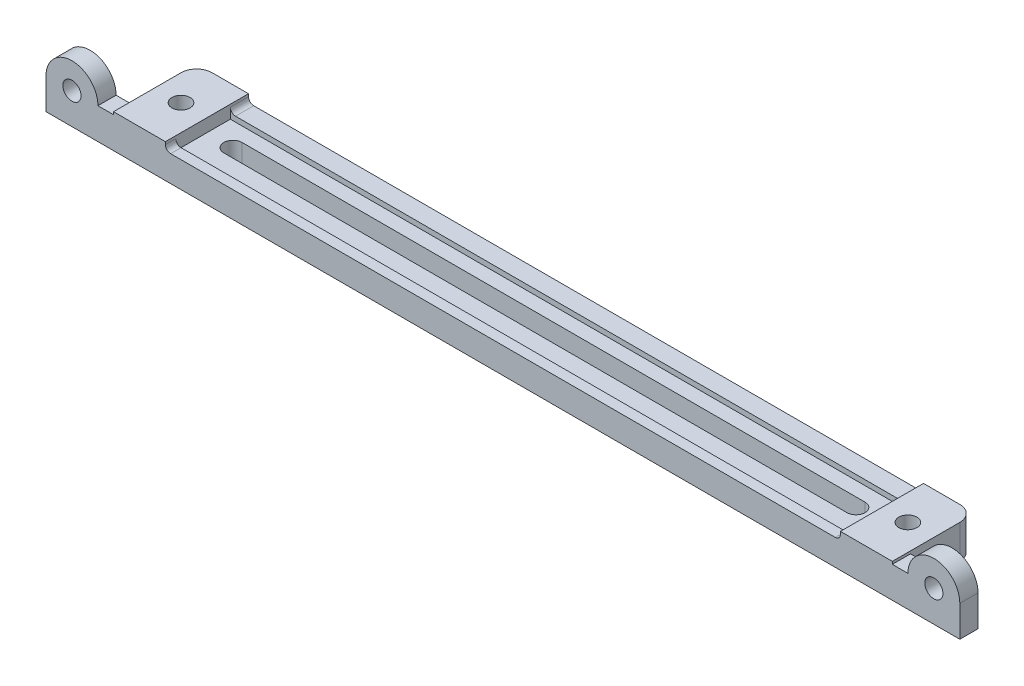
SolidWorks part; units mm, degrees
ref_plane "Front Plane" through (0, 0, 0) normal (0, 0, 1) x (1, 0, 0)
ref_plane "Top Plane" through (0, 0, 0) normal (0, 1, 0) x (1, 0, 0)
ref_plane "Right Plane" through (0, 0, 0) normal (1, 0, 0) x (0, 0, -1)
sketch "Sketch1" plane through (0, 0, 0) normal (0, 1, 0) x (1, 0, 0)
  line L0 (0, 0) -> (0, 8) construction
  line L1 (75, -8) -> (-75, -8)
  line L2 (75, -8) -> (75, 5)
  line L3 (72, 8) -> (-72, 8)
  line L4 (-75, -8) -> (-75, 5)
  line L5 (75, -8) -> (-75, 8) construction
  line L6 (75, 8) -> (-75, -8) construction
  line L8 (60, -1.75) -> (-60, -1.75)
  line L9 (60, -1.75) -> (60, 1.75)
  line L10 (60, 1.75) -> (-60, 1.75)
  line L11 (-60, -1.75) -> (-60, 1.75)
  line L12 (60, -1.75) -> (-60, 1.75) construction
  line L13 (60, 1.75) -> (-60, -1.75) construction
  circle A0 centre (-70, 0) radius 1.75
  circle A1 centre (70, 0) radius 1.75
  circle A2 centre (-60, 0) radius 1.75
  circle A3 centre (60, 0) radius 1.75
  arc A4 (72, 8) -> (75, 5) centre (72, 5) cw
  arc A5 (-72, 8) -> (-75, 5) centre (-72, 5) ccw
  point P0 (0, 0)
  dimension "D3" = 3.5
  dimension "D8" = 3
  dimension "D1" = 150
  dimension "D2" = 16
  dimension "D4" = 5
  dimension "D5" = 8
  dimension "D6" = 3.5
  dimension "D7" = 120
extrude "Boss-Extrude1" add sketch "Sketch1" along normal blind 4 contours L3 A5 L4 L1 L2 A4 L10 A3 L8 A2 A1 A0
sketch "Sketch2" plane through (0, 4, 0) normal (0, 1, 0) x (1, 0, 0)
  line L0 (-65, -8) -> (-65, 8)
  line L1 (75, -8) -> (-75, -8) construction
  line L2 (72, 8) -> (-72, 8) construction
  line L3 (65, -8) -> (65, 8)
  line L4 (75, -8) -> (75, 5) construction
  line L5 (-75, -8) -> (-75, 5) construction
  line L6 (-65, -6) -> (65, -6)
  line L7 (-65, 4.5) -> (65, 4.5)
  line L8 (75, -8) -> (65, -8)
  line L9 (-75, -8) -> (-75, 5)
  line L10 (-72, 8) -> (-65, 8)
  line L11 (-65, 8) -> (65, 8)
  line L12 (65, 8) -> (72, 8)
  line L13 (75, 5) -> (75, -8)
  line L14 (65, -8) -> (-65, -8)
  line L15 (-75, -8) -> (-65, -8)
  arc A0 (-75, 5) -> (-72, 8) centre (-72, 5) cw
  arc A1 (72, 8) -> (75, 5) centre (72, 5) cw
  circle A2 centre (70, 0) radius 1.75
  circle A3 centre (-70, 0) radius 1.75
  dimension "D1" = 10
  dimension "D2" = 10
  dimension "D3" = 2
  dimension "D4" = 10.5
extrude "Boss-Extrude2" add sketch "Sketch2" along normal blind 1
sketch "Sketch3" plane through (0, 5, 0) normal (0, 1, 0) x (1, 0, 0)
  line L0 (65, 4.5) -> (65, 8)
  line L1 (72, 8) -> (-72, 8) construction
  line L2 (65, -6) -> (65, -8)
  line L3 (-75, -8) -> (75, -8) construction
  line L4 (65, -8) -> (75, -8)
  line L5 (75, -8) -> (75, 5)
  line L6 (72, 8) -> (65, 8)
  line L7 (65, 4.5) -> (65, -6)
  line L8 (-65, 4.5) -> (-65, 8)
  line L9 (-65, 8) -> (-72, 8)
  line L10 (-75, 5) -> (-75, -8)
  line L11 (-75, -8) -> (-65, -8)
  line L12 (-65, -8) -> (-65, -6)
  line L13 (-65, -6) -> (-65, 4.5)
  arc A0 (75, 5) -> (72, 8) centre (72, 5) ccw
  arc A1 (-72, 8) -> (-75, 5) centre (-72, 5) ccw
  circle A2 centre (-70, 0) radius 1.75
  circle A3 centre (70, 0) radius 1.75
extrude "Boss-Extrude3" add sketch "Sketch3" along normal blind 1.5
fillet "Fillet1" radius 1 4 edges at (65, 5, -6.25) (65, 5, 7) (-65, 5, -6.25) (-65, 5, 7)
sketch "Sketch4" plane through (0, 0, 8) normal (0, 0, 1) x (1, 0, 0)
  line L0 (-75, 0) -> (-88, 0)
  line L1 (-88, 0) -> (-88, 6)
  line L2 (-78, 6) -> (-75, 6)
  line L3 (-75, 6.5) -> (-75, 0) construction
  line L4 (-75, 6) -> (-75, 0)
  line L5 (0, 0) -> (0, 5) construction
  line L6 (-64, 5) -> (64, 5) construction
  line L7 (75, 6) -> (75, 0)
  line L8 (78, 6) -> (75, 6)
  line L9 (88, 0) -> (88, 6)
  line L10 (75, 0) -> (88, 0)
  circle A0 centre (-83, 6) radius 1.75
  arc A1 (-88, 6) -> (-78, 6) centre (-83, 6) cw
  circle A2 centre (83, 6) radius 1.75
  arc A3 (88, 6) -> (78, 6) centre (83, 6) ccw
  line M14 (75, 0) -> (75, 6.5)
  line M22 (-75, 6.5) -> (-75, 0)
  dimension "D2" = 5
  dimension "D3" = 3.5
  dimension "D1" = 6
  dimension "D4" = 6
  dimension "D5" = 3
extrude "Boss-Extrude4" add sketch "Sketch4" against normal blind 3.5 contours A1 L1 L0 L2 A0 M22 | L9 A3 L8 L10 A2 M14
